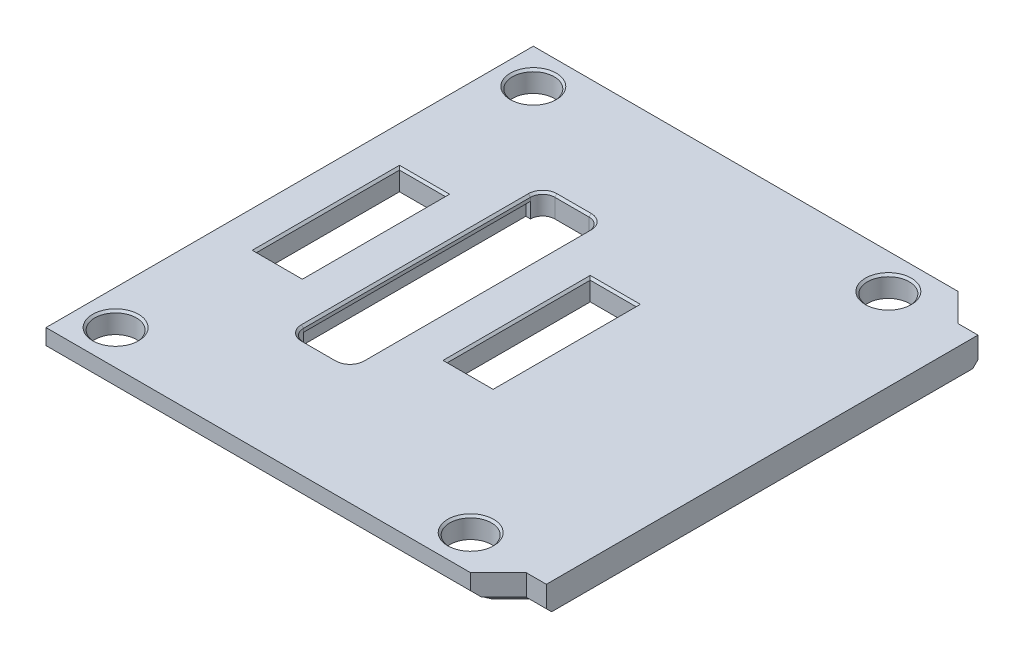
SolidWorks part; units mm, degrees
ref_plane "Front Plane" through (0, 0, 0) normal (0, 0, 1) x (1, 0, 0)
ref_plane "Top Plane" through (0, 0, 0) normal (0, 1, 0) x (1, 0, 0)
ref_plane "Right Plane" through (0, 0, 0) normal (1, 0, 0) x (0, 0, -1)
sketch "Sketch3" plane through (0, 0, 0) normal (0, 1, 0) x (1, 0, 0)
  line L0 (13.7, 0) -> (0, 0) construction
  line L1 (16.75, 10.025) -> (10.65, 10.025)
  line L2 (16.75, 10.025) -> (16.75, -10.025)
  line L3 (16.75, -10.025) -> (10.65, -10.025)
  line L4 (3.96, -16.3) -> (3.96, 16.3)
  line L5 (-2.46, -17.8) -> (2.46, -17.8)
  line L6 (-3.96, 16.3) -> (-3.96, -16.3)
  line L7 (2.46, 17.8) -> (-2.46, 17.8)
  line L8 (0, 17.8) -> (0, -17.8) construction
  line L9 (10.65, 10.025) -> (10.65, -10.025)
  line L10 (16.75, 10.025) -> (10.65, -10.025) construction
  line L11 (16.75, -10.025) -> (10.65, 10.025) construction
  line L12 (-16.75, -10.025) -> (-10.65, -10.025)
  line L13 (-16.75, 10.025) -> (-16.75, -10.025)
  line L14 (-16.75, 10.025) -> (-10.65, 10.025)
  line L15 (-10.65, 10.025) -> (-10.65, -10.025)
  arc A0 (-2.46, 17.8) -> (-3.96, 16.3) centre (-2.46, 16.3) ccw
  arc A1 (3.96, 16.3) -> (2.46, 17.8) centre (2.46, 16.3) ccw
  arc A2 (2.46, -17.8) -> (3.96, -16.3) centre (2.46, -16.3) ccw
  arc A3 (-3.96, -16.3) -> (-2.46, -17.8) centre (-2.46, -16.3) ccw
  point P9 (0, 0)
  point P23 (0, 0)
  dimension "D2" = 1.5
  dimension "D1" = 13.7
  dimension "D3" = 7.92
  dimension "D4" = 20.05
  dimension "D5" = 6.1
  dimension "D6" = 35.6
sketch "Sketch21" plane through (0, 0, 0) normal (0, 1, 0) x (1, 0, 0)
  line L1 (38.5, 35) -> (-22.5, 35)
  line L7 (38.5, 35) -> (42.5, 31)
  line L8 (-22.5, 35) -> (-22.5, -35)
  line L9 (-22.5, 0) -> (0, 0) construction
  line L10 (0, 0) -> (38.5, 0) construction
  line L11 (38.5, -35) -> (38.5, 35) construction
  line L12 (38.5, -35) -> (-22.5, -35)
  line L13 (42.5, 31) -> (45.375, 31)
  line L14 (45.375, 31) -> (45.375, -31)
  line L15 (45.375, 0) -> (38.5, 0) construction
  line L16 (42.5, -31) -> (45.375, -31)
  line L17 (38.5, -35) -> (42.5, -31)
  line L26 (16.75, 10.025) -> (10.65, 10.025)
  line L27 (10.65, 10.025) -> (10.65, -10.025)
  line L28 (10.65, -10.025) -> (16.75, -10.025)
  line L29 (16.75, -10.025) -> (16.75, 10.025)
  line L30 (16.75, 10.025) -> (10.65, 10.025) construction
  line L31 (10.65, 10.025) -> (10.65, -10.025) construction
  line L32 (10.65, -10.025) -> (16.75, -10.025) construction
  line L33 (16.75, -10.025) -> (16.75, 10.025) construction
  line L34 (-10.4, -10.275) -> (-10.4, 10.275)
  line L35 (-10.4, 10.275) -> (-17, 10.275)
  line L36 (-17, 10.275) -> (-17, -10.275)
  line L37 (-17, -10.275) -> (-10.4, -10.275)
  line L38 (-16.75, -10.025) -> (-10.65, -10.025)
  line L39 (-10.65, -10.025) -> (-10.65, 10.025)
  line L40 (-10.65, 10.025) -> (-16.75, 10.025)
  line L41 (-16.75, 10.025) -> (-16.75, -10.025)
  line L42 (-16.75, -10.025) -> (-10.65, -10.025) construction
  line L43 (-10.65, -10.025) -> (-10.65, 10.025) construction
  line L44 (-10.65, 10.025) -> (-16.75, 10.025) construction
  line L45 (-16.75, 10.025) -> (-16.75, -10.025) construction
  line L46 (-3.96, 16.3) -> (-3.96, -16.3)
  line L47 (2.46, 17.8) -> (-2.46, 17.8)
  line L48 (3.96, -16.3) -> (3.96, 16.3)
  line L49 (-2.46, -17.8) -> (2.46, -17.8)
  line L50 (-3.96, 16.3) -> (-3.96, -16.3) construction
  line L51 (2.46, 17.8) -> (-2.46, 17.8) construction
  line L52 (3.96, -16.3) -> (3.96, 16.3) construction
  line L53 (-2.46, -17.8) -> (2.46, -17.8) construction
  line L54 (-4.21, 16.3) -> (-4.21, -16.3)
  line L55 (-2.46, -18.05) -> (2.46, -18.05)
  line L56 (4.21, -16.3) -> (4.21, 16.3)
  line L57 (2.46, 18.05) -> (-2.46, 18.05)
  line L58 (17, 10.275) -> (10.4, 10.275)
  line L59 (10.4, 10.275) -> (10.4, -10.275)
  line L60 (10.4, -10.275) -> (17, -10.275)
  line L61 (17, -10.275) -> (17, 10.275)
  circle A4 centre (-17.5, 30) radius 1.6 construction
  circle A5 centre (33.5, 30) radius 1.6 construction
  circle A6 centre (33.5, -30) radius 1.6 construction
  circle A7 centre (-17.5, -30) radius 1.6 construction
  circle A8 centre (-17.5, 30) radius 3
  circle A9 centre (-17.5, -30) radius 3
  circle A10 centre (33.5, -30) radius 3
  circle A11 centre (33.5, 30) radius 3
  arc A12 (-4.21, -16.3) -> (-2.46, -18.05) centre (-2.46, -16.3) ccw
  arc A13 (2.46, -18.05) -> (4.21, -16.3) centre (2.46, -16.3) ccw
  arc A14 (4.21, 16.3) -> (2.46, 18.05) centre (2.46, 16.3) ccw
  arc A15 (-2.46, 18.05) -> (-4.21, 16.3) centre (-2.46, 16.3) ccw
  arc A16 (-2.46, 17.8) -> (-3.96, 16.3) centre (-2.46, 16.3) ccw
  arc A17 (3.96, 16.3) -> (2.46, 17.8) centre (2.46, 16.3) ccw
  arc A18 (2.46, -17.8) -> (3.96, -16.3) centre (2.46, -16.3) ccw
  arc A19 (-3.96, -16.3) -> (-2.46, -17.8) centre (-2.46, -16.3) ccw
  arc A20 (-2.46, 17.8) -> (-3.96, 16.3) centre (-2.46, 16.3) ccw construction
  arc A21 (3.96, 16.3) -> (2.46, 17.8) centre (2.46, 16.3) ccw construction
  arc A22 (2.46, -17.8) -> (3.96, -16.3) centre (2.46, -16.3) ccw construction
  arc A23 (-3.96, -16.3) -> (-2.46, -17.8) centre (-2.46, -16.3) ccw construction
  dimension "D16" = 3.2
  dimension "D2" = 6
  dimension "D3" = 0
  dimension "D4" = 0
  dimension "D5" = 0
  dimension "D6" = 0.25
  dimension "D9" = 22.5
  dimension "D10" = 61
  dimension "D11" = 35
  dimension "D12" = 5
  dimension "D13" = 5
  dimension "D14" = 5
  dimension "D15" = 5
  dimension "D17" = 45
  dimension "D18" = 4
  dimension "D19" = 2.875
extrude "Boss-Extrude3" add sketch "Sketch21" along normal blind 3
sketch "Sketch28" plane through (0, 0, 0) normal (0, -1, 0) x (1, 0, 0)
  line L9 (42.5, -31) -> (45.375, -31) construction
  line L13 (39.5, 34) -> (39.5, -34)
  line L14 (38.5, 35) -> (39.5, 34) construction
  line L17 (45.375, -31) -> (45.375, 31) construction
  line L18 (42.5, 31) -> (45.375, 31) construction
  line L19 (38.5, 35) -> (38.5, -35) construction
  line L20 (42.5, -31) -> (45.375, -31)
  line L21 (45.375, -31) -> (45.375, 31)
  line L22 (42.5, 31) -> (45.375, 31)
  line L23 (38.5, 35) -> (38.5, -35) construction
  line L24 (38.5, -35) -> (42.5, -31) construction
  line L25 (39.5, -34) -> (42.5, -31)
  line L26 (38.5, 35) -> (42.5, 31) construction
  line L27 (39.5, 34) -> (42.5, 31)
  line L28 (38.5, -35) -> (39.5, -34) construction
  dimension "D1" = 1
extrude "Boss-Extrude2" add sketch "Sketch28" along normal blind 0.8
sketch "Sketch29" plane through (0, 0, 0) normal (0, -1, 0) x (1, 0, 0)
  line L0 (-4.21, 16.3) -> (-4.875, 16.3)
  line L1 (-4.875, 16.3) -> (-4.875, -16.3)
  line L2 (-4.875, -16.3) -> (-4.21, -16.3)
  line L3 (-4.21, -16.3) -> (4.21, -16.3)
  line L4 (4.21, -16.3) -> (4.875, -16.3)
  line L5 (4.875, -16.3) -> (4.875, 16.3)
  line L6 (4.875, 16.3) -> (4.21, 16.3)
  line L7 (4.21, 16.3) -> (-4.21, 16.3)
  line L8 (0, 16.3) -> (0, 0) construction
  line L9 (0, 0) -> (4.875, 0) construction
  line L10 (0, 0) -> (-4.875, 0) construction
  arc A0 (-4.21, -16.3) -> (-2.46, -18.05) centre (-2.46, -16.3) ccw construction
  dimension "D1" = 9.75
extrude "Cut-Extrude1" cut sketch "Sketch29" against normal blind 2.2
sketch "Sketch30" plane through (0, 0, 0) normal (0, -1, 0) x (1, 0, 0)
  line L0 (30, -14) -> (30, 35) construction
  line L2 (-22.5, 35) -> (38.5, 35) construction
  text T0 "Ms4p" font "Microsoft Sans Serif" height 8
  dimension "D1" = 30
  dimension "D2" = 14
extrude "Cut-Extrude2" cut sketch "Sketch30" against normal blind 1
chamfer "Chamfer1" distance 0.3 angle 45 20 edges at (33.5, 3, 33) (-17.5, 3, 33) (-17.5, 3, -27) (33.5, 3, -27) (17, 3, 0) (13.7, 3, -10.275) (10.4, 3, 0) (13.7, 3, 10.275) (-13.7, 3, 10.275) (-17, 3, 0) (-10.4, 3, 0) (-13.7, 3, -10.275) (0, 3, 18.05) (3.6974, 3, 17.5374) (-3.6974, 3, 17.5374) (4.21, 3, 0) (-4.21, 3, 0) (3.6974, 3, -17.5374) (-3.6974, 3, -17.5374) (0, 3, -18.05)
chamfer "Chamfer2" distance 0.75 angle 45 8 edges at (41, -0.8, -32.5) (43.9375, -0.8, -31) (45.375, -0.8, 0) (43.9375, -0.8, 31) (41, -0.8, 32.5) (8, 0, -35) (8, 0, 35) (-22.5, 0, 0)
